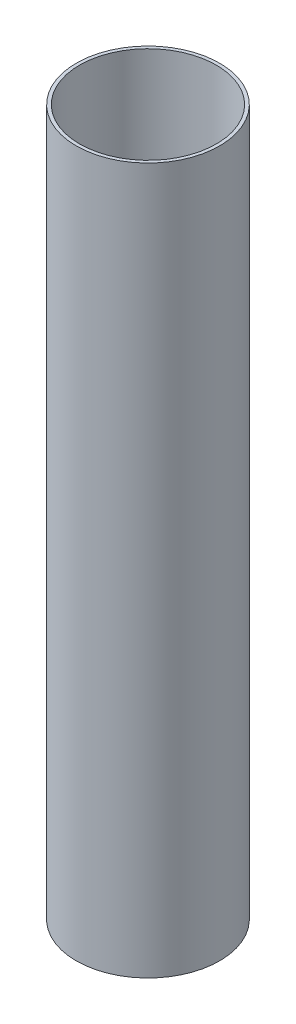
SolidWorks part; units mm, degrees
ref_plane "前视基准面" through (0, 0, 0) normal (0, 0, 1) x (1, 0, 0)
ref_plane "上视基准面" through (0, 0, 0) normal (0, 1, 0) x (1, 0, 0)
ref_plane "右视基准面" through (0, 0, 0) normal (1, 0, 0) x (0, 0, -1)
sketch "草图1" plane through (0, 0, 0) normal (0, 1, 0) x (1, 0, 0)
  circle A0 centre (0, 0) radius 32.5
  dimension "D1" = 65
extrude "凸台-拉伸1" add sketch "草图1" along normal blind 320 contours A0
sketch "草图2" plane through (0, 320, 0) normal (0, 1, 0) x (1, 0, 0)
  circle A0 centre (0, 0) radius 31
  dimension "D1" = 62
extrude "切除-拉伸1" cut sketch "草图2" against normal through all
